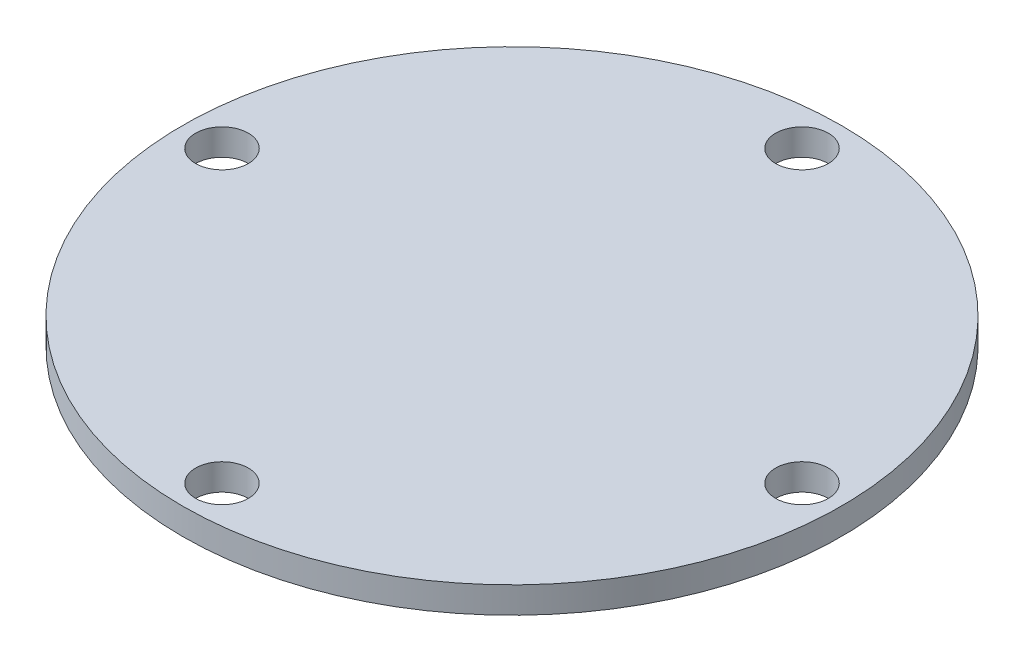
SolidWorks part; units mm, degrees
ref_plane "Ön Düzlem" through (0, 0, 0) normal (0, 0, 1) x (1, 0, 0)
ref_plane "Üst Düzlem" through (0, 0, 0) normal (0, 1, 0) x (1, 0, 0)
ref_plane "Sağ Düzlem" through (0, 0, 0) normal (1, 0, 0) x (0, 0, -1)
sketch "Çizim1" plane through (0, 0, 0) normal (0, 1, 0) x (1, 0, 0)
  circle A0 centre (0, 0) radius 25
  circle A2 centre (-22, 0) radius 2
  circle A3 centre (22, 0) radius 2
  dimension "D1" = 50
  dimension "D2" = 4
  dimension "D3" = 44
  dimension "D4" = 22
extrude "Yükseklik-Ekstrüzyon1" add sketch "Çizim1" along normal blind 2
sketch "Çizim3" plane through (0, 2, 0) normal (0, 1, 0) x (1, 0, 0)
  circle A0 centre (0, 22) radius 1.9988
  circle A1 centre (0, -22) radius 1.9988
  dimension "D1" = 3.9976
  dimension "D2" = 22
  dimension "D3" = 44
extrude "Kes-Ekstrüzyon1" cut sketch "Çizim3" against normal blind 2
